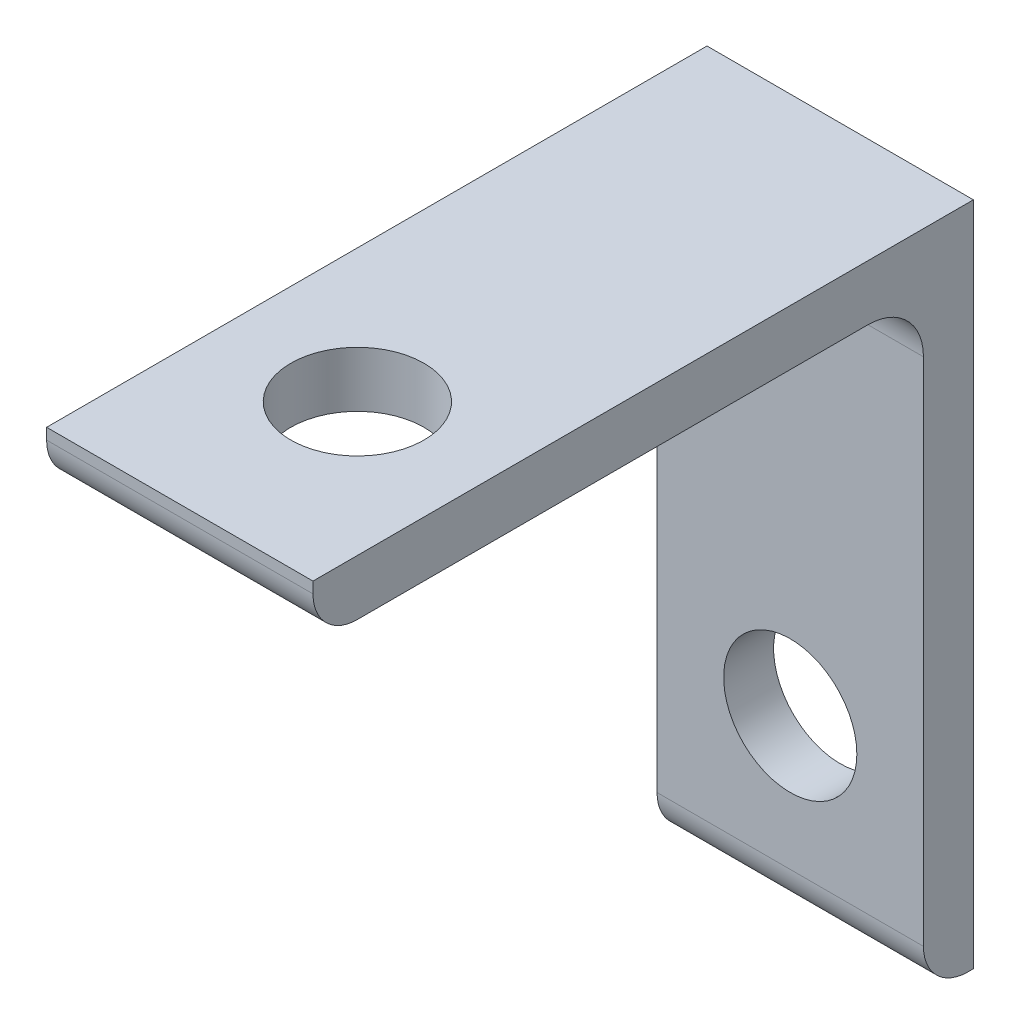
SolidWorks part; units mm, degrees
material "Liga de aço"
ref_plane "Plano frontal" through (0, 0, 0) normal (0, 0, 1) x (1, 0, 0)
ref_plane "Plano superior" through (0, 0, 0) normal (0, 1, 0) x (1, 0, 0)
ref_plane "Plano direito" through (0, 0, 0) normal (1, 0, 0) x (0, 0, -1)
sketch "Esboço1" plane through (0, 0, 0) normal (0, 0, 1) x (1, 0, 0)
  line L1 (-17.5035, -3.4533) -> (-16.3035, -3.4533)
  line L2 (-17.5035, -3.4533) -> (-17.5035, -6.4533)
  line L3 (-17.5035, -6.4533) -> (-16.3035, -6.4533)
  line L4 (-16.3035, -3.4533) -> (-16.3035, -6.4533)
  dimension "D1" = 3
  dimension "D2" = 1.2
extrude "Ressalto-extrusão1" add sketch "Esboço1" along normal blind 0.225
sketch "Esboço2" plane through (-17.5035, 0, 0) normal (-1, 0, 0) x (0, 0, 1)
  line L1 (0.225, -3.4533) -> (2.975, -3.4533)
  line L2 (0.225, -3.4533) -> (0.225, -3.7033)
  line L3 (0.225, -3.7033) -> (2.975, -3.7033)
  line L4 (2.975, -3.4533) -> (2.975, -3.7033)
  dimension "D1" = 2.75
  dimension "D2" = 0.25
extrude "Ressalto-extrusão2" add sketch "Esboço2" against normal blind 1.2
sketch "Esboço6" plane through (-17.5035, 0, 0) normal (-1, 0, 0) x (0, 0, 1)
  line L0 (0.225, -3.9533) -> (0.225, -3.7033)
  line L1 (0.475, -3.7033) -> (0.225, -3.7033)
  line L6 (0, -3.4533) -> (0, -6.4533)
  line L7 (0, -6.4533) -> (0.225, -6.4533)
  line L8 (0.225, -6.4533) -> (0.225, -3.7033)
  line L9 (0.225, -3.7033) -> (2.975, -3.7033)
  line L10 (2.975, -3.7033) -> (2.975, -3.4533)
  line L11 (2.975, -3.4533) -> (0, -3.4533)
  line L12 (0, -3.4533) -> (0, -6.4533)
  line L13 (0, -6.4533) -> (0.225, -6.4533)
  line L14 (0.225, -6.4533) -> (0.225, -3.9533)
  line L15 (0.475, -3.7033) -> (2.975, -3.7033)
  line L16 (2.975, -3.7033) -> (2.975, -3.4533)
  line L17 (2.975, -3.4533) -> (0, -3.4533)
  arc A0 (0.475, -3.7033) -> (0.225, -3.9533) centre (0.475, -3.9533) ccw
  line M11 (0.225, -6.4533) -> (0.225, -3.7033)
  line M12 (0.225, -3.7033) -> (2.975, -3.7033)
  dimension "D2" = 0.25
  dimension "D1" = 0
extrude "Ressalto-extrusão3" add sketch "Esboço6" against normal blind 1.2 contours A0 M12 M11
sketch "Esboço7" plane through (-17.5035, 0, 0) normal (-1, 0, 0) x (0, 0, 1)
  line L0 (0.025, -6.4533) -> (0.225, -6.4533)
  line L1 (0.225, -6.4533) -> (0.225, -6.2533)
  line L2 (2.775, -3.7033) -> (2.975, -3.7033)
  line L3 (2.975, -3.7033) -> (2.975, -3.5033)
  line L6 (0.225, -6.4533) -> (0.225, -3.9533)
  line L7 (0.475, -3.7033) -> (2.975, -3.7033)
  line L8 (2.975, -3.7033) -> (2.975, -3.4533)
  line L9 (2.975, -3.4533) -> (0, -3.4533)
  line L10 (0, -3.4533) -> (0, -6.4533)
  line L11 (0, -6.4533) -> (0.225, -6.4533)
  line L12 (0.225, -6.2533) -> (0.225, -3.9533)
  line L13 (0.475, -3.7033) -> (2.775, -3.7033)
  line L14 (2.975, -3.5033) -> (2.975, -3.4533)
  line L15 (2.975, -3.4533) -> (0, -3.4533)
  line L16 (0, -3.4533) -> (0, -6.4533)
  line L17 (0, -6.4533) -> (0.025, -6.4533)
  arc A0 (2.775, -3.7033) -> (2.975, -3.5033) centre (2.775, -3.5033) ccw
  arc A1 (0.475, -3.7033) -> (0.225, -3.9533) centre (0.475, -3.9533) ccw
  arc A2 (0.475, -3.7033) -> (0.225, -3.9533) centre (0.475, -3.9533) ccw
  arc A3 (0.225, -6.2533) -> (0.025, -6.4533) centre (0.025, -6.2533) cw
  line M8 (0.225, -6.4533) -> (0.225, -3.9533)
  line M10 (0.475, -3.7033) -> (2.975, -3.7033)
  line M11 (2.975, -3.7033) -> (2.975, -3.4533)
  line M14 (0, -6.4533) -> (0.225, -6.4533)
  dimension "D2" = 0.2
  dimension "D3" = 0.2
  dimension "D1" = 0
extrude "Corte-extrusão1" cut sketch "Esboço7" against normal blind 1.2 contours A0 M10 M11 | A3 M8 M14
sketch "Esboço8" plane through (0, 0, 0.225) normal (0, 0, 1) x (1, 0, 0)
  line L0 (-17.5035, -6.2533) -> (-16.3035, -5.0533) construction
  line L1 (-16.3035, -6.2533) -> (-16.3035, -3.9533) construction
  circle A0 centre (-16.9035, -5.6533) radius 0.6 construction
  circle A1 centre (-16.9035, -5.6533) radius 0.3
extrude "Corte-extrusão2" cut sketch "Esboço8" against normal blind 1.2
sketch "Esboço9" plane through (0, -3.7033, 0) normal (0, -1, 0) x (1, 0, 0)
  line L0 (-16.3035, 2.775) -> (-17.5035, 1.575) construction
  line L1 (-17.5035, 0.475) -> (-17.5035, 2.775) construction
  circle A0 centre (-16.9035, 2.175) radius 0.6 construction
  circle A1 centre (-16.9035, 2.175) radius 0.3
extrude "Corte-extrusão3" cut sketch "Esboço9" against normal blind 1.2
